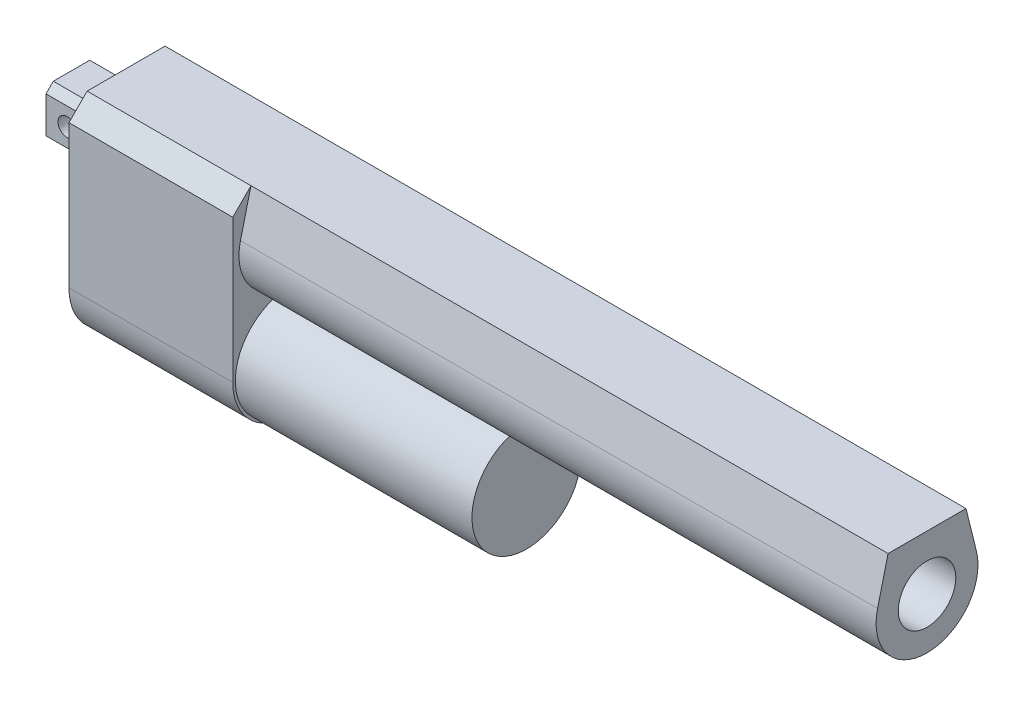
SolidWorks part; units mm, degrees
ref_plane "Front Plane" through (0, 0, 0) normal (0, 0, 1) x (1, 0, 0)
ref_plane "Top Plane" through (0, 0, 0) normal (0, 1, 0) x (1, 0, 0)
ref_plane "Right Plane" through (0, 0, 0) normal (1, 0, 0) x (0, 0, -1)
sketch "Sketch1" plane through (0, 0, 0) normal (1, 0, 0) x (0, 0, -1)
  line L0 (-13.589, 19.05) -> (13.589, 19.05)
  line L1 (-19.939, -37.211) -> (-19.939, 12.7)
  line L2 (-19.939, 12.7) -> (-13.589, 19.05)
  line L3 (0, 0) -> (0, 19.05) construction
  line L4 (19.939, -37.211) -> (19.939, 12.7)
  line L5 (19.939, 12.7) -> (13.589, 19.05)
  line L6 (-19.939, 12.7) -> (-19.939, 19.05) construction
  line L7 (-19.939, 19.05) -> (-13.589, 19.05) construction
  arc A0 (-19.939, -37.211) -> (19.939, -37.211) centre (0, -37.211) ccw
  point P7 (0, -57.15)
  dimension "D1" = 39.878
  dimension "D2" = 19.05
  dimension "D3" = 76.2
  dimension "D4" = 6.35
extrude "Boss-Extrude1" add sketch "Sketch1" along normal blind 57.15
sketch "Sketch2" plane through (57.15, 0, 0) normal (1, 0, 0) x (0, 0, -1)
  circle A0 centre (0, -37.211) radius 19.05
  arc A1 (-19.939, -37.211) -> (19.939, -37.211) centre (0, -37.211) ccw construction
  dimension "D1" = 38.1
extrude "Boss-Extrude2" add sketch "Sketch2" along normal blind 82.55
sketch "Sketch3" plane through (0, 0, 0) normal (-1, 0, 0) x (0, 0, 1)
  line L0 (-6.35, 8.89) -> (6.35, 8.89)
  line L1 (6.35, 8.89) -> (8.89, 6.35)
  line L2 (8.89, 6.35) -> (8.89, -6.35)
  line L3 (8.89, -6.35) -> (6.35, -8.89)
  line L4 (6.35, -8.89) -> (-6.35, -8.89)
  line L5 (-6.35, -8.89) -> (-8.89, -6.35)
  line L6 (-8.89, -6.35) -> (-8.89, 6.35)
  line L7 (-8.89, 6.35) -> (-6.35, 8.89)
  line L8 (-8.89, 6.35) -> (-8.89, 8.89) construction
  line L9 (-8.89, 8.89) -> (-6.35, 8.89) construction
  line L10 (0, 8.89) -> (0, -8.89) construction
  dimension "D1" = 17.78
  dimension "D2" = 2.54
extrude "Boss-Extrude3" add sketch "Sketch3" along normal blind 19.05
sketch "Sketch4" plane through (0, 0, 8.89) normal (0, 0, 1) x (1, 0, 0)
  line L0 (-19.05, 0) -> (-11.684, 0) construction
  line L1 (-19.05, -6.35) -> (-19.05, 6.35) construction
  circle A0 centre (-11.684, 0) radius 3.175
  dimension "D2" = 6.35
  dimension "D1" = 7.366
extrude "Cut-Extrude1" cut sketch "Sketch4" against normal through all
sketch "Sketch5" plane through (57.15, 0, 0) normal (1, 0, 0) x (0, 0, -1)
  line L0 (-13.589, 19.05) -> (13.589, 19.05)
  line L1 (13.589, 19.05) -> (-13.589, 19.05) construction
  line L2 (-13.589, 19.05) -> (-17.2558, 4.2855)
  line L3 (13.589, 19.05) -> (17.2558, 4.2855)
  arc A0 (-17.2558, 4.2855) -> (17.2558, 4.2855) centre (0, 0) ccw
  point P2 (0, 19.05)
  dimension "D1" = 17.78
extrude "Boss-Extrude4" add sketch "Sketch5" along normal blind 222.25
sketch "Sketch6" plane through (279.4, 0, 0) normal (1, 0, 0) x (0, 0, -1)
  circle A0 centre (0, 0) radius 10.033
  arc A1 (-17.2558, 4.2855) -> (17.2558, 4.2855) centre (0, 0) ccw construction
  dimension "D1" = 20.066
extrude "Cut-Extrude2" cut sketch "Sketch6" against normal blind 203.2
